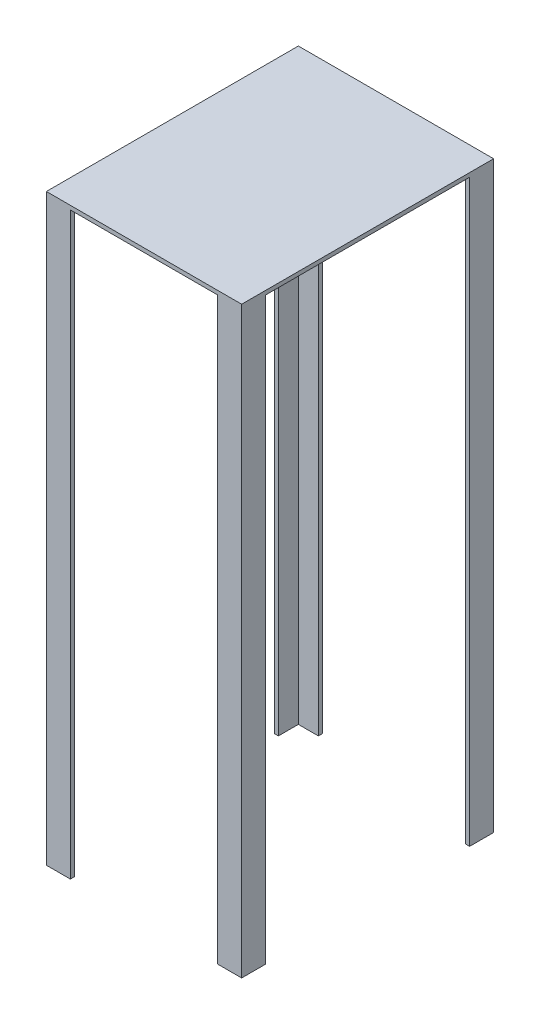
SolidWorks part; units mm, degrees
ref_plane "Alzado" through (0, 0, 0) normal (0, 0, 1) x (1, 0, 0)
ref_plane "Planta" through (0, 0, 0) normal (0, 1, 0) x (1, 0, 0)
ref_plane "Vista lateral" through (0, 0, 0) normal (1, 0, 0) x (0, 0, -1)
sketch "Croquis2" plane through (0, 0, 0) normal (0, 1, 0) x (1, 0, 0)
  line L1 (0, 0) -> (310, 0)
  line L2 (0, 0) -> (0, 400)
  line L3 (0, 400) -> (310, 400)
  line L4 (310, 0) -> (310, 400)
  dimension "D1" = 310
  dimension "D2" = 400
extrude "Saliente-Extruir1" add sketch "Croquis2" against normal blind 6.35
sketch "Croquis3" plane through (0, -6.35, 0) normal (0, -1, 0) x (1, 0, 0)
  line L0 (0, 0) -> (38.1, 0)
  line L1 (0, 0) -> (310, 0) construction
  line L2 (0, 0) -> (0, -38.1)
  line L3 (0, -400) -> (0, 0) construction
  line L4 (6.35, -6.35) -> (6.35, -38.1)
  line L5 (6.35, -6.35) -> (38.1, -6.35)
  line L6 (38.1, -6.35) -> (38.1, 0)
  line L7 (6.35, -38.1) -> (0, -38.1)
  line L8 (155, 0) -> (155, -200) construction
  line L9 (310, -200) -> (0, -200) construction
  line L10 (303.65, -38.1) -> (310, -38.1)
  line L11 (271.9, -6.35) -> (271.9, 0)
  line L12 (303.65, -6.35) -> (271.9, -6.35)
  line L13 (303.65, -6.35) -> (303.65, -38.1)
  line L14 (310, 0) -> (310, -38.1)
  line L15 (310, 0) -> (271.9, 0)
  line L16 (310, -400) -> (271.9, -400)
  line L17 (310, -400) -> (310, -361.9)
  line L18 (303.65, -393.65) -> (303.65, -361.9)
  line L19 (303.65, -393.65) -> (271.9, -393.65)
  line L20 (271.9, -393.65) -> (271.9, -400)
  line L21 (303.65, -361.9) -> (310, -361.9)
  line L22 (6.35, -361.9) -> (0, -361.9)
  line L23 (38.1, -393.65) -> (38.1, -400)
  line L24 (6.35, -393.65) -> (38.1, -393.65)
  line L25 (6.35, -393.65) -> (6.35, -361.9)
  line L26 (0, -400) -> (0, -361.9)
  line L27 (0, -400) -> (38.1, -400)
  dimension "D1" = 38.1
  dimension "D2" = 38.1
  dimension "D3" = 6.35
extrude "Saliente-Extruir2" add sketch "Croquis3" along normal blind 920
